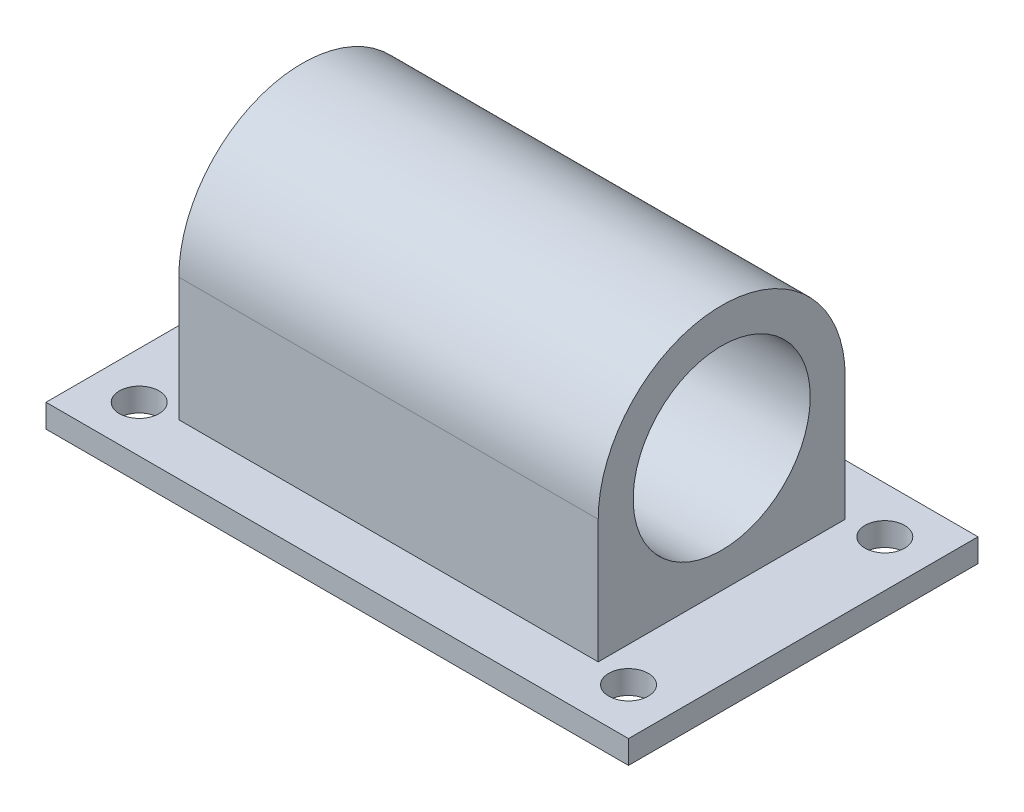
SolidWorks part; units mm, degrees
ref_plane "Piano frontale" through (0, 0, 0) normal (0, 0, 1) x (1, 0, 0)
ref_plane "Piano superiore" through (0, 0, 0) normal (0, 1, 0) x (1, 0, 0)
ref_plane "Piano destro" through (0, 0, 0) normal (1, 0, 0) x (0, 0, -1)
sketch "Schizzo1" plane through (0, 0, 0) normal (0, 1, 0) x (1, 0, 0)
  line L1 (-25, 15) -> (25, 15)
  line L2 (-25, 15) -> (-25, -15)
  line L3 (-25, -15) -> (25, -15)
  line L4 (25, 15) -> (25, -15)
  dimension "D1" = 50
  dimension "D2" = 30
extrude "Estrusione-Estrusione1" add sketch "Schizzo1" along normal blind 2
sketch "Schizzo2" plane through (0, 0, 0) normal (1, 0, 0) x (0, 0, -1)
  line L1 (-10.6, 12.6) -> (-10.6, 2)
  line L3 (-15, 2) -> (15, 2) construction
  line L4 (-10.6, 2) -> (10.6, 2)
  line L5 (10.6, 12.6) -> (10.6, 2)
  circle A0 centre (0, 12.6) radius 7.6
  arc A1 (10.6, 12.6) -> (-10.6, 12.6) centre (0, 12.6) ccw
  point P3 (0, 2)
  point P6 (0, 2)
  dimension "D1" = 15.2
extrude "Estrusione-Estrusione2" add sketch "Schizzo2" along normal mid plane 36 separate body
sketch "Schizzo3" plane through (0, 2, 0) normal (0, 1, 0) x (1, 0, 0)
  line L0 (25, 15) -> (-25, 15) construction
  line L1 (-25, 15) -> (-25, -15) construction
  line L2 (0, 15) -> (0, -15) construction
  line L3 (-25, -15) -> (25, -15) construction
  line L4 (-25, 0) -> (25, 0) construction
  line L5 (25, -15) -> (25, 15) construction
  circle A0 centre (-21, 11) radius 1.7
  circle A1 centre (21, 11) radius 1.7
  circle A2 centre (-21, -11) radius 1.7
  circle A3 centre (21, -11) radius 1.7
  dimension "D1" = 3.4
  dimension "D3" = 4
  dimension "D2" = 4
extrude "Taglio-Estrusione1" cut sketch "Schizzo3" against normal through all
